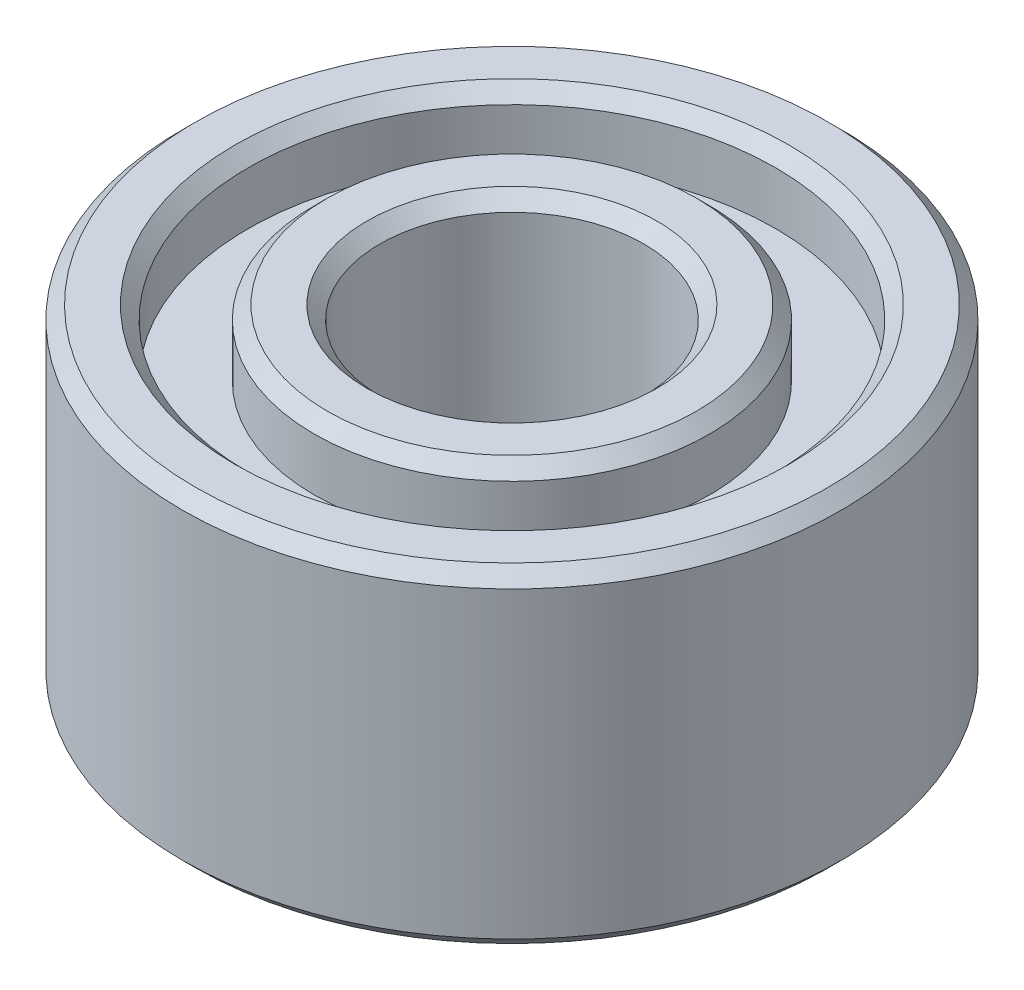
SolidWorks part; units mm, degrees
ref_plane "Front Plane" through (0, 0, 0) normal (0, 0, 1) x (1, 0, 0)
ref_plane "Top Plane" through (0, 0, 0) normal (0, 1, 0) x (1, 0, 0)
ref_plane "Right Plane" through (0, 0, 0) normal (1, 0, 0) x (0, 0, -1)
sketch "Sketch1" plane through (0, 0, 0) normal (0, 1, 0) x (1, 0, 0)
  circle A0 centre (0, 0) radius 2.5
  circle A1 centre (0, 0) radius 1
  dimension "D1" = 5
  dimension "D2" = 2
extrude "Boss-Extrude1" add sketch "Sketch1" along normal blind 2.5
sketch "Sketch2" plane through (0, 2.5, 0) normal (0, 1, 0) x (1, 0, 0)
  circle A0 centre (0, 0) radius 1.5
  circle A1 centre (0, 0) radius 2
  dimension "D1" = 4
  dimension "D2" = 3
extrude "Cut-Extrude1" cut sketch "Sketch2" against normal blind 0.5
sketch "Sketch3" plane through (0, 0, 0) normal (0, -1, 0) x (1, 0, 0)
  circle A0 centre (0, 0) radius 1.5
  circle A1 centre (0, 0) radius 2
  dimension "D1" = 4
  dimension "D2" = 3
extrude "Cut-Extrude2" cut sketch "Sketch3" against normal blind 0.5
chamfer "Chamfer1" distance 0.1 angle 45 6 edges at (0, 0, 2.5) (0, 0, -2) (0, 2.5, 1.5) (0, 2.5, 1) (0, 2.5, 2.5) (0, 2.5, 2)
